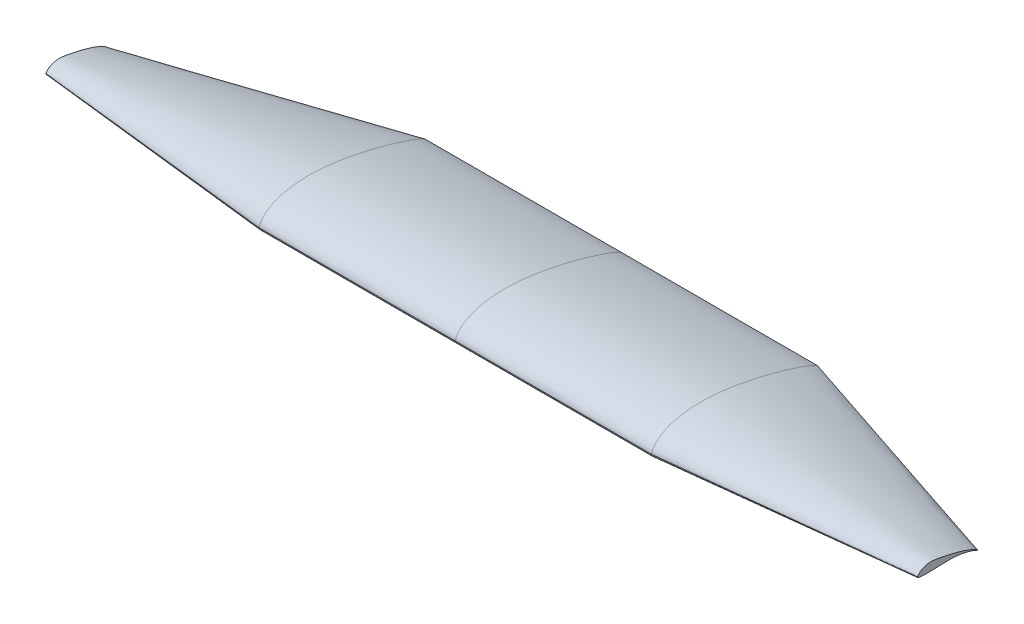
SolidWorks part; units mm, degrees
ref_plane "Front Plane" through (0, 0, 0) normal (0, 0, 1) x (1, 0, 0)
ref_plane "Top Plane" through (0, 0, 0) normal (0, 1, 0) x (1, 0, 0)
ref_plane "Right Plane" through (0, 0, 0) normal (1, 0, 0) x (0, 0, -1)
curve "Curve1"
  spline degree 3 poles (25.4, 0, 0) (25.372, 0.0127, 0) (25.2661, 0.0607, 0) (25.0476, 0.1708, 0) (24.7083, 0.3401, 0) (24.2485, 0.5327, 0) (23.6688, 0.7355, 0) (22.9732, 0.9551, 0) (22.1692, 1.1923, 0) (21.2673, 1.441, 0) (20.2799, 1.6974, 0) (19.2194, 1.9565, 0) (18.0986, 2.2117, 0) (16.9309, 2.4579, 0) (15.7293, 2.689, 0) (14.5068, 2.8993, 0) (13.2761, 3.0831, 0) (12.0499, 3.2358, 0) (10.8399, 3.3523, 0) (9.6581, 3.4292, 0) (8.5146, 3.4627, 0) (7.4185, 3.4471, 0) (6.3776, 3.3826, 0) (5.3986, 3.269, 0) (4.4879, 3.1072, 0) (3.6513, 2.8996, 0) (2.8934, 2.65, 0) (2.2179, 2.3636, 0) (1.6288, 2.0454, 0) (1.1277, 1.7031, 0) (0.7172, 1.3448, 0) (0.396, 0.9813, 0) (0.1698, 0.6239, 0) (0.0242, 0.2862, 0) (0.0082, 0.064, 0) (0.001, -0.0371, 0) knots 0 0 0 0 0.003392 0.012836 0.027012 0.045249 0.067819 0.094788 0.125784 0.160358 0.198063 0.238408 0.280877 0.324962 0.370154 0.415962 0.4619 0.507515 0.552371 0.596075 0.638248 0.678633 0.717052 0.753345 0.787382 0.819093 0.848434 0.875385 0.89998 0.922244 0.942232 0.960009 0.975549 0.988878 1 1 1 1
curve "Curve2"
  spline degree 3 poles (0.001, -0.0371, 0) (0.0123, -0.12, 0) (0.0361, -0.2949, 0) (0.317, -0.4639, 0) (0.6929, -0.5692, 0) (1.2135, -0.6662, 0) (1.8581, -0.7318, 0) (2.6218, -0.773, 0) (3.494, -0.7837, 0) (4.468, -0.7549, 0) (5.5382, -0.6866, 0) (6.7006, -0.5792, 0) (7.9499, -0.4372, 0) (9.2786, -0.2733, 0) (10.6742, -0.0995, 0) (12.1205, 0.0739, 0) (13.5986, 0.2368, 0) (15.0876, 0.3793, 0) (16.5646, 0.4933, 0) (18.0052, 0.5722, 0) (19.384, 0.6119, 0) (20.6751, 0.6102, 0) (21.8534, 0.5686, 0) (22.8944, 0.4921, 0) (23.7738, 0.3865, 0) (24.4667, 0.2603, 0) (24.9566, 0.1368, 0) (25.2443, 0.0508, 0) (25.3692, 0.0101, 0) (25.4, 0, 0) knots 0 0 0 0 0.009279 0.019577 0.035039 0.055495 0.080743 0.110498 0.144404 0.182203 0.223831 0.269139 0.318001 0.370105 0.424881 0.481621 0.539567 0.597874 0.655635 0.711901 0.765703 0.816085 0.862086 0.902834 0.937485 0.965078 0.984713 0.996231 1 1 1 1
curve "Curve3"
  spline degree 3 poles (25.4, 0, 0) (25.3455, 0.0436, 0) (25.2116, 0.1507, 0) (24.9968, 0.3329, 0) (24.7179, 0.5192, 0) (24.3838, 0.6915, 0) (23.9854, 0.8618, 0) (23.5127, 1.0388, 0) (22.9617, 1.2228, 0) (22.3389, 1.411, 0) (21.6587, 1.6, 0) (20.9384, 1.7859, 0) (20.194, 1.9655, 0) (19.4371, 2.1364, 0) (18.6752, 2.2963, 0) (17.9118, 2.4438, 0) (17.147, 2.5781, 0) (16.3791, 2.6991, 0) (15.605, 2.8074, 0) (14.8209, 2.9041, 0) (14.0236, 2.9909, 0) (13.211, 3.0702, 0) (12.3837, 3.1443, 0) (11.5456, 3.2153, 0) (10.7042, 3.2841, 0) (9.8699, 3.3504, 0) (9.0549, 3.4114, 0) (8.2722, 3.4638, 0) (7.5336, 3.5033, 0) (6.8455, 3.5244, 0) (6.2068, 3.521, 0) (5.6107, 3.49, 0) (5.0497, 3.4308, 0) (4.5176, 3.3429, 0) (4.0108, 3.2266, 0) (3.5272, 3.0823, 0) (3.0666, 2.9114, 0) (2.6305, 2.7158, 0) (2.222, 2.4994, 0) (1.8461, 2.2685, 0) (1.5081, 2.0322, 0) (1.2124, 1.7997, 0) (0.9603, 1.579, 0) (0.7502, 1.3741, 0) (0.5779, 1.1854, 0) (0.4381, 1.0119, 0) (0.3252, 0.8525, 0) (0.2341, 0.7057, 0) (0.1613, 0.5701, 0) (0.1038, 0.4444, 0) (0.0597, 0.3272, 0) (0.028, 0.2175, 0) (0.0067, 0.1145, 0) (0.002, 0.0475, 0) (-0.0002, 0.0153, 0) knots 0 0 0 0 0.007668 0.018842 0.030923 0.044413 0.060081 0.078505 0.099861 0.123886 0.149975 0.177417 0.205607 0.234111 0.262657 0.29113 0.319536 0.347958 0.376531 0.40541 0.434747 0.464647 0.495109 0.526002 0.557051 0.587854 0.61795 0.646847 0.674037 0.699207 0.722467 0.744193 0.764751 0.784417 0.803402 0.821846 0.839822 0.857338 0.87432 0.890569 0.905775 0.91961 0.931872 0.942562 0.95184 0.959925 0.96702 0.973296 0.978892 0.983919 0.988474 0.992632 0.996456 1 1 1 1
curve "Curve4"
  spline degree 3 poles (-0.0002, 0.0153, 0) (-0.0001, -0.0154, 0) (0.0001, -0.0769, 0) (0.0214, -0.1684, 0) (0.075, -0.2496, 0) (0.16, -0.3047, 0) (0.2619, -0.3388, 0) (0.378, -0.3612, 0) (0.51, -0.376, 0) (0.6617, -0.3855, 0) (0.8391, -0.3907, 0) (1.051, -0.391, 0) (1.3098, -0.3853, 0) (1.6325, -0.3717, 0) (2.0384, -0.3474, 0) (2.5403, -0.3101, 0) (3.1345, -0.2569, 0) (3.8031, -0.1837, 0) (4.5269, -0.0871, 0) (5.2942, 0.0299, 0) (6.0973, 0.1597, 0) (6.9255, 0.2967, 0) (7.7654, 0.437, 0) (8.6054, 0.5766, 0) (9.4374, 0.712, 0) (10.2578, 0.8409, 0) (11.0657, 0.9608, 0) (11.8615, 1.0703, 0) (12.6459, 1.1675, 0) (13.4202, 1.2512, 0) (14.1858, 1.3204, 0) (14.9439, 1.3743, 0) (15.6958, 1.4123, 0) (16.4425, 1.4338, 0) (17.1849, 1.4384, 0) (17.9237, 1.4258, 0) (18.659, 1.3959, 0) (19.3904, 1.3486, 0) (20.1162, 1.2841, 0) (20.833, 1.2027, 0) (21.5342, 1.1057, 0) (22.209, 0.9944, 0) (22.8431, 0.872, 0) (23.4213, 0.7417, 0) (23.9328, 0.606, 0) (24.3746, 0.4668, 0) (24.7496, 0.3244, 0) (25.0872, 0.1744, 0) (25.2937, 0.0593, 0) (25.4, 0, 0) knots 0 0 0 0 0.003545 0.0071 0.01071 0.014494 0.01858 0.023086 0.028144 0.033926 0.04066 0.048671 0.058426 0.070592 0.086022 0.105451 0.128789 0.155005 0.183229 0.21323 0.244762 0.277305 0.310312 0.343241 0.375773 0.407796 0.43928 0.470229 0.500682 0.530682 0.560295 0.589573 0.618576 0.647349 0.675954 0.704423 0.732791 0.761051 0.789175 0.817054 0.84447 0.871027 0.896137 0.919138 0.939558 0.957324 0.972672 0.985929 1 1 1 1
sketch "Sketch4" plane through (0, 0, 0) normal (0, 0, 1) x (1, 0, 0)
  spline S0 degree 3 poles (-1185.8345, -1591.3505) (49.1871, -0.0243) (32.3891, -5.936) (24.9968, 0.3329) (24.7179, 0.5192) (24.3838, 0.6915) (23.9854, 0.8618) (23.5127, 1.0388) (22.9617, 1.2228) (22.3389, 1.411) (21.6587, 1.6) (20.9384, 1.7859) (20.194, 1.9655) (19.4371, 2.1364) (18.6752, 2.2963) (17.9118, 2.4438) (17.147, 2.5781) (16.3791, 2.6991) (15.605, 2.8074) (14.8209, 2.9041) (14.0236, 2.9909) (13.211, 3.0702) (12.3837, 3.1443) (11.5456, 3.2153) (10.7042, 3.2841) (9.8699, 3.3504) (9.0549, 3.4114) (8.2722, 3.4638) (7.5336, 3.5033) (6.8455, 3.5244) (6.2068, 3.521) (5.6107, 3.49) (5.0497, 3.4308) (4.5176, 3.3429) (4.0108, 3.2266) (3.5272, 3.0823) (3.0666, 2.9114) (2.6305, 2.7158) (2.222, 2.4994) (1.8461, 2.2685) (1.5081, 2.0322) (1.2124, 1.7997) (0.9603, 1.579) (0.7502, 1.3741) (0.5779, 1.1854) (0.4381, 1.0119) (0.3252, 0.8525) (0.2341, 0.7057) (0.1613, 0.5701) (0.1038, 0.4444) (0.0597, 0.3272) (0.028, 0.2175) (-0.6393, -3.0024) (19.7265, -8.824) (-1985.4173, 239.6089) knots -1.033249 -1.033249 -1.033249 -1.033249 0.007668 0.018842 0.030923 0.044413 0.060081 0.078505 0.099861 0.123886 0.149975 0.177417 0.205607 0.234111 0.262657 0.29113 0.319536 0.347958 0.376531 0.40541 0.434747 0.464647 0.495109 0.526002 0.557051 0.587854 0.61795 0.646847 0.674037 0.699207 0.722467 0.744193 0.764751 0.784417 0.803402 0.821846 0.839822 0.857338 0.87432 0.890569 0.905775 0.91961 0.931872 0.942562 0.95184 0.959925 0.96702 0.973296 0.978892 0.983919 0.988474 0.992632 0.996456 1.348806 1.348806 1.348806 1.348806 only from (25.4, 0) to (-0.0002, 0.0153) construction
  spline S1 degree 3 poles (-1996.9046, -109.2454) (24.0142, 6.4939) (-0.5867, 2.4404) (0.0214, -0.1684) (0.075, -0.2496) (0.16, -0.3047) (0.2619, -0.3388) (0.378, -0.3612) (0.51, -0.376) (0.6617, -0.3855) (0.8391, -0.3907) (1.051, -0.391) (1.3098, -0.3853) (1.6325, -0.3717) (2.0384, -0.3474) (2.5403, -0.3101) (3.1345, -0.2569) (3.8031, -0.1837) (4.5269, -0.0871) (5.2942, 0.0299) (6.0973, 0.1597) (6.9255, 0.2967) (7.7654, 0.437) (8.6054, 0.5766) (9.4374, 0.712) (10.2578, 0.8409) (11.0657, 0.9608) (11.8615, 1.0703) (12.6459, 1.1675) (13.4202, 1.2512) (14.1858, 1.3204) (14.9439, 1.3743) (15.6958, 1.4123) (16.4425, 1.4338) (17.1849, 1.4384) (17.9237, 1.4258) (18.659, 1.3959) (19.3904, 1.3486) (20.1162, 1.2841) (20.833, 1.2027) (21.5342, 1.1057) (22.209, 0.9944) (22.8431, 0.872) (23.4213, 0.7417) (23.9328, 0.606) (24.3746, 0.4668) (24.7496, 0.3244) (32.9485, -3.3172) (27.4813, -33.5723) (953.9511, 1771.2477) knots -0.294627 -0.294627 -0.294627 -0.294627 0.003545 0.0071 0.01071 0.014494 0.01858 0.023086 0.028144 0.033926 0.04066 0.048671 0.058426 0.070592 0.086022 0.105451 0.128789 0.155005 0.183229 0.21323 0.244762 0.277305 0.310312 0.343241 0.375773 0.407796 0.43928 0.470229 0.500682 0.530682 0.560295 0.589573 0.618576 0.647349 0.675954 0.704423 0.732791 0.761051 0.789175 0.817054 0.84447 0.871027 0.896137 0.919138 0.939558 0.957324 0.972672 0.985929 1.993687 1.993687 1.993687 1.993687 only from (-0.0002, 0.0153) to (25.4, 0) construction
  spline S2 degree 3 poles (25.4, 0) (25.3455, 0.0436) (25.2116, 0.1507) (24.9968, 0.3329) (24.7179, 0.5192) (24.3838, 0.6915) (23.9854, 0.8618) (23.5127, 1.0388) (22.9617, 1.2228) (22.3389, 1.411) (21.6587, 1.6) (20.9384, 1.7859) (20.194, 1.9655) (19.4371, 2.1364) (18.6752, 2.2963) (17.9118, 2.4438) (17.147, 2.5781) (16.3791, 2.6991) (15.605, 2.8074) (14.8209, 2.9041) (14.0236, 2.9909) (13.211, 3.0702) (12.3837, 3.1443) (11.5456, 3.2153) (10.7042, 3.2841) (9.8699, 3.3504) (9.0549, 3.4114) (8.2722, 3.4638) (7.5336, 3.5033) (6.8455, 3.5244) (6.2068, 3.521) (5.6107, 3.49) (5.0497, 3.4308) (4.5176, 3.3429) (4.0108, 3.2266) (3.5272, 3.0823) (3.0666, 2.9114) (2.6305, 2.7158) (2.222, 2.4994) (1.8461, 2.2685) (1.5081, 2.0322) (1.2124, 1.7997) (0.9603, 1.579) (0.7502, 1.3741) (0.5779, 1.1854) (0.4381, 1.0119) (0.3252, 0.8525) (0.2341, 0.7057) (0.1613, 0.5701) (0.1038, 0.4444) (0.0597, 0.3272) (0.028, 0.2175) (0.0067, 0.1145) (0.002, 0.0475) (-0.0002, 0.0153) knots 0 0 0 0 0.007668 0.018842 0.030923 0.044413 0.060081 0.078505 0.099861 0.123886 0.149975 0.177417 0.205607 0.234111 0.262657 0.29113 0.319536 0.347958 0.376531 0.40541 0.434747 0.464647 0.495109 0.526002 0.557051 0.587854 0.61795 0.646847 0.674037 0.699207 0.722467 0.744193 0.764751 0.784417 0.803402 0.821846 0.839822 0.857338 0.87432 0.890569 0.905775 0.91961 0.931872 0.942562 0.95184 0.959925 0.96702 0.973296 0.978892 0.983919 0.988474 0.992632 0.996456 1 1 1 1
  spline S3 degree 3 poles (-0.0002, 0.0153) (-0.0001, -0.0154) (0.0001, -0.0769) (0.0214, -0.1684) (0.075, -0.2496) (0.16, -0.3047) (0.2619, -0.3388) (0.378, -0.3612) (0.51, -0.376) (0.6617, -0.3855) (0.8391, -0.3907) (1.051, -0.391) (1.3098, -0.3853) (1.6325, -0.3717) (2.0384, -0.3474) (2.5403, -0.3101) (3.1345, -0.2569) (3.8031, -0.1837) (4.5269, -0.0871) (5.2942, 0.0299) (6.0973, 0.1597) (6.9255, 0.2967) (7.7654, 0.437) (8.6054, 0.5766) (9.4374, 0.712) (10.2578, 0.8409) (11.0657, 0.9608) (11.8615, 1.0703) (12.6459, 1.1675) (13.4202, 1.2512) (14.1858, 1.3204) (14.9439, 1.3743) (15.6958, 1.4123) (16.4425, 1.4338) (17.1849, 1.4384) (17.9237, 1.4258) (18.659, 1.3959) (19.3904, 1.3486) (20.1162, 1.2841) (20.833, 1.2027) (21.5342, 1.1057) (22.209, 0.9944) (22.8431, 0.872) (23.4213, 0.7417) (23.9328, 0.606) (24.3746, 0.4668) (24.7496, 0.3244) (25.0872, 0.1744) (25.2937, 0.0593) (25.4, 0) knots 0 0 0 0 0.003545 0.0071 0.01071 0.014494 0.01858 0.023086 0.028144 0.033926 0.04066 0.048671 0.058426 0.070592 0.086022 0.105451 0.128789 0.155005 0.183229 0.21323 0.244762 0.277305 0.310312 0.343241 0.375773 0.407796 0.43928 0.470229 0.500682 0.530682 0.560295 0.589573 0.618576 0.647349 0.675954 0.704423 0.732791 0.761051 0.789175 0.817054 0.84447 0.871027 0.896137 0.919138 0.939558 0.957324 0.972672 0.985929 1 1 1 1
sketch "Sketch1" plane through (0, 0, 0) normal (0, 0, 1) x (1, 0, 0)
  spline S0 degree 3 poles (-1716.1238, -1026.9999) (43.62, 33.158) (-2.8325, 1.4304) (0.317, -0.4639) (0.6929, -0.5692) (1.2135, -0.6662) (1.8581, -0.7318) (2.6218, -0.773) (3.494, -0.7837) (4.468, -0.7549) (5.5382, -0.6866) (6.7006, -0.5792) (7.9499, -0.4372) (9.2786, -0.2733) (10.6742, -0.0995) (12.1205, 0.0739) (13.5986, 0.2368) (15.0876, 0.3793) (16.5646, 0.4933) (18.0052, 0.5722) (19.384, 0.6119) (20.6751, 0.6102) (21.8534, 0.5686) (22.8944, 0.4921) (23.7738, 0.3865) (24.4667, 0.2603) (24.9566, 0.1368) (31.9392, -1.9512) (35.8158, -13.1556) (656.9828, 1897.5367) knots -0.357758 -0.357758 -0.357758 -0.357758 0.009279 0.019577 0.035039 0.055495 0.080743 0.110498 0.144404 0.182203 0.223831 0.269139 0.318001 0.370105 0.424881 0.481621 0.539567 0.597874 0.655635 0.711901 0.765703 0.816085 0.862086 0.902834 0.937485 0.965078 0.984713 0.996231 1.812784 1.812784 1.812784 1.812784 only from (0.001, -0.0371) to (25.4, 0) construction
  spline S1 degree 3 poles (-816.7312, -1813.9846) (40.2514, 5.3756) (30.2436, -2.4476) (25.0476, 0.1708) (24.7083, 0.3401) (24.2485, 0.5327) (23.6688, 0.7355) (22.9732, 0.9551) (22.1692, 1.1923) (21.2673, 1.441) (20.2799, 1.6974) (19.2194, 1.9565) (18.0986, 2.2117) (16.9309, 2.4579) (15.7293, 2.689) (14.5068, 2.8993) (13.2761, 3.0831) (12.0499, 3.2358) (10.8399, 3.3523) (9.6581, 3.4292) (8.5146, 3.4627) (7.4185, 3.4471) (6.3776, 3.3826) (5.3986, 3.269) (4.4879, 3.1072) (3.6513, 2.8996) (2.8934, 2.65) (2.2179, 2.3636) (1.6288, 2.0454) (1.1277, 1.7031) (0.7172, 1.3448) (0.396, 0.9813) (0.1698, 0.6239) (-2.024, -4.4643) (37.9783, -18.4695) (-1958.3981, 404.8989) knots -0.615231 -0.615231 -0.615231 -0.615231 0.003392 0.012836 0.027012 0.045249 0.067819 0.094788 0.125784 0.160358 0.198063 0.238408 0.280877 0.324962 0.370154 0.415962 0.4619 0.507515 0.552371 0.596075 0.638248 0.678633 0.717052 0.753345 0.787382 0.819093 0.848434 0.875385 0.89998 0.922244 0.942232 0.960009 0.975549 0.988878 1.562488 1.562488 1.562488 1.562488 only from (25.4, 0) to (0.001, -0.0371) construction
  spline S2 degree 3 poles (0.001, -0.0371) (0.0123, -0.12) (0.0361, -0.2949) (0.317, -0.4639) (0.6929, -0.5692) (1.2135, -0.6662) (1.8581, -0.7318) (2.6218, -0.773) (3.494, -0.7837) (4.468, -0.7549) (5.5382, -0.6866) (6.7006, -0.5792) (7.9499, -0.4372) (9.2786, -0.2733) (10.6742, -0.0995) (12.1205, 0.0739) (13.5986, 0.2368) (15.0876, 0.3793) (16.5646, 0.4933) (18.0052, 0.5722) (19.384, 0.6119) (20.6751, 0.6102) (21.8534, 0.5686) (22.8944, 0.4921) (23.7738, 0.3865) (24.4667, 0.2603) (24.9566, 0.1368) (25.2443, 0.0508) (25.3692, 0.0101) (25.4, 0) knots 0 0 0 0 0.009279 0.019577 0.035039 0.055495 0.080743 0.110498 0.144404 0.182203 0.223831 0.269139 0.318001 0.370105 0.424881 0.481621 0.539567 0.597874 0.655635 0.711901 0.765703 0.816085 0.862086 0.902834 0.937485 0.965078 0.984713 0.996231 1 1 1 1
  spline S3 degree 3 poles (25.4, 0) (25.372, 0.0127) (25.2661, 0.0607) (25.0476, 0.1708) (24.7083, 0.3401) (24.2485, 0.5327) (23.6688, 0.7355) (22.9732, 0.9551) (22.1692, 1.1923) (21.2673, 1.441) (20.2799, 1.6974) (19.2194, 1.9565) (18.0986, 2.2117) (16.9309, 2.4579) (15.7293, 2.689) (14.5068, 2.8993) (13.2761, 3.0831) (12.0499, 3.2358) (10.8399, 3.3523) (9.6581, 3.4292) (8.5146, 3.4627) (7.4185, 3.4471) (6.3776, 3.3826) (5.3986, 3.269) (4.4879, 3.1072) (3.6513, 2.8996) (2.8934, 2.65) (2.2179, 2.3636) (1.6288, 2.0454) (1.1277, 1.7031) (0.7172, 1.3448) (0.396, 0.9813) (0.1698, 0.6239) (0.0242, 0.2862) (0.0082, 0.064) (0.001, -0.0371) knots 0 0 0 0 0.003392 0.012836 0.027012 0.045249 0.067819 0.094788 0.125784 0.160358 0.198063 0.238408 0.280877 0.324962 0.370154 0.415962 0.4619 0.507515 0.552371 0.596075 0.638248 0.678633 0.717052 0.753345 0.787382 0.819093 0.848434 0.875385 0.89998 0.922244 0.942232 0.960009 0.975549 0.988878 1 1 1 1
sketch "Sketch2" plane through (0, 0, 0) normal (1, 0, 0) x (0, 0, -1)
  line L0 (0, 0) -> (574.8782, -20.8789) construction
  line L1 (-1000, 0) -> (49000, 0) construction
  spline S0 degree 3 poles (0, 0) (0.1844, -1.886) (0.5733, -5.865) (6.7875, -9.9296) (15.2046, -12.6352) (26.9028, -15.2746) (41.4372, -17.3102) (58.686, -18.896) (78.4169, -19.884) (100.4863, -20.0651) (124.7652, -19.4351) (151.1663, -17.9989) (179.5632, -15.852) (209.7738, -13.2791) (241.5094, -10.5383) (274.391, -7.8521) (307.983, -5.4281) (341.8055, -3.4758) (375.3321, -2.159) (408.0036, -1.606) (439.243, -1.8866) (468.4639, -3.0273) (495.0952, -4.9768) (518.5901, -7.5991) (538.4024, -10.7407) (553.9782, -14.1892) (564.9608, -17.4025) (571.3975, -19.5953) (574.1897, -20.625) (574.8782, -20.8789) knots 0 0 0 0 0.009279 0.019577 0.035039 0.055495 0.080743 0.110498 0.144404 0.182203 0.223831 0.269139 0.318001 0.370105 0.424881 0.481621 0.539567 0.597874 0.655635 0.711901 0.765703 0.816085 0.862086 0.902834 0.937485 0.965078 0.984713 0.996231 1 1 1 1
  spline S1 degree 3 poles (574.8782, -20.8789) (574.2556, -20.5679) (571.8998, -19.3911) (567.048, -16.7118) (559.513, -12.5906) (549.2719, -7.8384) (536.326, -2.7532) (520.7693, 2.8138) (502.775, 8.868) (482.5771, 15.2687) (460.4485, 21.9166) (436.6678, 28.6863) (411.5198, 35.4212) (385.3015, 41.9909) (358.3033, 48.2497) (330.8147, 54.0549) (303.1186, 59.2662) (275.496, 63.7715) (248.212, 67.4434) (221.5288, 70.1931) (195.6776, 71.9291) (170.8574, 72.5129) (147.2422, 71.9443) (124.9876, 70.2111) (104.2394, 67.3257) (85.1258, 63.3439) (67.7594, 58.3425) (52.2277, 52.4391) (38.6213, 45.7396) (26.9881, 38.4216) (17.3911, 30.6622) (9.8111, 22.712) (4.3846, 14.8166) (0.8, 7.297) (0.2501, 2.2814) (0, 0) knots 0 0 0 0 0.003392 0.012836 0.027012 0.045249 0.067819 0.094788 0.125784 0.160358 0.198063 0.238408 0.280877 0.324962 0.370154 0.415962 0.4619 0.507515 0.552371 0.596075 0.638248 0.678633 0.717052 0.753345 0.787382 0.819093 0.848434 0.875385 0.89998 0.922244 0.942232 0.960009 0.975549 0.988878 1 1 1 1
  dimension "D1" = 574.8782
  dimension "D2" = 2.08
extrude "Boss-Extrude2" add sketch "Sketch2" along normal blind 680.085
ref_plane "Plane4" through (1511.3, 0, 0) normal (1, 0, 0) x (0, 0, -1)
sketch "Sketch3" plane through (0, 0, 0) normal (0, 1, 0) x (1, 0, 0)
  line L0 (0, 143.7195) -> (1743.4724, 143.7195) construction
  line L1 (0, 574.8782) -> (0, 0) construction
  line L2 (0, 0) -> (0, 143.7195) construction
  line L3 (0, 143.7195) -> (0, 287.4391) construction
  line L4 (0, 287.4391) -> (0, 431.1586) construction
  line L5 (0, 431.1586) -> (0, 574.8782) construction
sketch "Sketch5" plane through (1511.3, 0, 0) normal (1, 0, 0) x (0, 0, -1)
  line L0 (91.459, 1.7609) -> (300.5011, -23.6544) construction
  line L1 (-1000, 1.7609) -> (49000, 1.7609) construction
  line L2 (0, 3.5219) -> (0, 0) construction
  line L3 (91.459, 1.7609) -> (91.459, 0) construction
  line L4 (91.459, 0) -> (143.7195, 0) construction
  line L5 (300.501, 0) -> (300.5011, -23.6544) construction
  line L6 (143.7195, 0) -> (195.9801, 0) construction
  line L7 (195.9801, 0) -> (248.2406, 0) construction
  line L8 (248.2406, 0) -> (300.501, 0) construction
  spline S0 degree 3 poles (300.5011, -23.6544) (300.0958, -23.2413) (299.1002, -22.2264) (297.5135, -20.5132) (295.4042, -18.702) (292.8258, -16.9516) (289.7164, -15.1529) (286.0015, -13.2252) (281.6498, -11.1627) (276.7117, -8.9931) (271.3012, -6.7607) (265.5582, -4.5132) (259.6095, -2.2936) (253.5503, -0.1341) (247.4389, 1.9405) (241.302, 3.9148) (235.1413, 5.7814) (228.9417, 7.5422) (222.6779, 9.2039) (216.3211, 10.7807) (209.8449, 12.2891) (203.2356, 13.7504) (196.5001, 15.184) (189.673, 16.6029) (182.8167, 18.0074) (176.0159, 19.3831) (169.3684, 20.6971) (162.9784, 21.9074) (156.9388, 22.9679) (151.2966, 23.8264) (146.0361, 24.4347) (141.0995, 24.7732) (136.4228, 24.8441) (131.9562, 24.6508) (127.6688, 24.1978) (123.5449, 23.4916) (119.5836, 22.5439) (115.7994, 21.368) (112.2223, 19.9935) (108.8983, 18.4677) (105.8808, 16.8589) (103.2157, 15.2399) (100.9214, 13.6749) (98.9882, 12.197) (97.3824, 10.8155) (96.0591, 9.5273) (94.9705, 8.3273) (94.0751, 7.2096) (93.3405, 6.1662) (92.7421, 5.1887) (92.2628, 4.2681) (91.8927, 3.3968) (91.6145, 2.5704) (91.5095, 2.0238) (91.459, 1.7609) knots 0 0 0 0 0.007668 0.018842 0.030923 0.044413 0.060081 0.078505 0.099861 0.123886 0.149975 0.177417 0.205607 0.234111 0.262657 0.29113 0.319536 0.347958 0.376531 0.40541 0.434747 0.464647 0.495109 0.526002 0.557051 0.587854 0.61795 0.646847 0.674037 0.699207 0.722467 0.744193 0.764751 0.784417 0.803402 0.821846 0.839822 0.857338 0.87432 0.890569 0.905775 0.91961 0.931872 0.942562 0.95184 0.959925 0.96702 0.973296 0.978892 0.983919 0.988474 0.992632 0.996456 1 1 1 1
  spline S1 degree 3 poles (91.459, 1.7609) (91.4293, 1.5082) (91.3696, 1.002) (91.454, 0.2276) (91.8142, -0.4943) (92.4591, -1.0326) (93.264, -1.4149) (94.1972, -1.715) (95.2684, -1.9681) (96.5076, -2.1973) (97.963, -2.4164) (99.7066, -2.6296) (101.8422, -2.8405) (104.5118, -3.0498) (107.8769, -3.2544) (112.0448, -3.447) (116.988, -3.6008) (122.564, -3.6635) (128.6176, -3.589) (135.0493, -3.3905) (141.7883, -3.1218) (148.7414, -2.8182) (155.7941, -2.5) (162.8463, -2.1875) (169.829, -1.901) (176.7098, -1.6573) (183.4789, -1.4744) (190.1372, -1.3661) (196.69, -1.3471) (203.1465, -1.4292) (209.5165, -1.6213) (215.8103, -1.9327) (222.0364, -2.3685) (228.2036, -2.9352) (234.3183, -3.6365) (240.3864, -4.4758) (246.4086, -5.4539) (252.3814, -6.5713) (258.2913, -7.8245) (264.11, -9.2082) (269.7844, -10.705) (275.2278, -12.2926) (280.3244, -13.9314) (284.9536, -15.5798) (289.0288, -17.2056) (292.526, -18.7913) (295.4705, -20.3371) (298.1, -21.9075) (299.685, -23.0606) (300.5011, -23.6544) knots 0 0 0 0 0.003545 0.0071 0.01071 0.014494 0.01858 0.023086 0.028144 0.033926 0.04066 0.048671 0.058426 0.070592 0.086022 0.105451 0.128789 0.155005 0.183229 0.21323 0.244762 0.277305 0.310312 0.343241 0.375773 0.407796 0.43928 0.470229 0.500682 0.530682 0.560295 0.589573 0.618576 0.647349 0.675954 0.704423 0.732791 0.761051 0.789175 0.817054 0.84447 0.871027 0.896137 0.919138 0.939558 0.957324 0.972672 0.985929 1 1 1 1
  point P7 (0, 1.7609)
  dimension "D1" = 209.042
  dimension "D2" = 25.4153
sketch "Sketch6" plane through (680.085, 0, 0) normal (1, 0, 0) x (0, 0, -1)
  spline S2 degree 3 poles (-673.7077, -2745.8479) (684.4763, -29.9694) (616.59, -44.0701) (567.048, -16.7118) (559.513, -12.5906) (549.2719, -7.8384) (536.326, -2.7532) (520.7693, 2.8138) (502.775, 8.868) (482.5771, 15.2687) (460.4485, 21.9166) (436.6678, 28.6863) (411.5198, 35.4212) (385.3015, 41.9909) (358.3033, 48.2497) (330.8147, 54.0549) (303.1186, 59.2662) (275.496, 63.7715) (248.212, 67.4434) (221.5288, 70.1931) (195.6776, 71.9291) (170.8574, 72.5129) (147.2422, 71.9443) (124.9876, 70.2111) (104.2394, 67.3257) (85.1258, 63.3439) (67.7594, 58.3425) (52.2277, 52.4391) (38.6213, 45.7396) (26.9881, 38.4216) (17.3911, 30.6622) (9.8111, 22.712) (4.3846, 14.8166) (-19.6237, -35.5476) (132.5736, -127.4912) (-2936.2723, 603.3427) knots -0.248804 -0.248804 -0.248804 -0.248804 0.003392 0.012836 0.027012 0.045249 0.067819 0.094788 0.125784 0.160358 0.198063 0.238408 0.280877 0.324962 0.370154 0.415962 0.4619 0.507515 0.552371 0.596075 0.638248 0.678633 0.717052 0.753345 0.787382 0.819093 0.848434 0.875385 0.89998 0.922244 0.942232 0.960009 0.975549 0.988878 1.227859 1.227859 1.227859 1.227859 only from (574.8782, -20.8789) to (0, 0)
  spline S3 degree 3 poles (-2661.3608, -1381.1653) (163.9668, 151.0666) (-25.1742, 10.9758) (6.7875, -9.9296) (15.2046, -12.6352) (26.9028, -15.2746) (41.4372, -17.3102) (58.686, -18.896) (78.4169, -19.884) (100.4863, -20.0651) (124.7652, -19.4351) (151.1663, -17.9989) (179.5632, -15.852) (209.7738, -13.2791) (241.5094, -10.5383) (274.391, -7.8521) (307.983, -5.4281) (341.8055, -3.4758) (375.3321, -2.159) (408.0036, -1.606) (439.243, -1.8866) (468.4639, -3.0273) (495.0952, -4.9768) (518.5901, -7.5991) (538.4024, -10.7407) (553.9782, -14.1892) (564.9608, -17.4025) (631.9494, -40.2234) (682.4818, -97.1332) (1776.5148, 2723.7464) knots -0.145177 -0.145177 -0.145177 -0.145177 0.009279 0.019577 0.035039 0.055495 0.080743 0.110498 0.144404 0.182203 0.223831 0.269139 0.318001 0.370105 0.424881 0.481621 0.539567 0.597874 0.655635 0.711901 0.765703 0.816085 0.862086 0.902834 0.937485 0.965078 0.984713 0.996231 1.328518 1.328518 1.328518 1.328518 only from (0, 0) to (574.8782, -20.8789)
  spline S4 degree 3 poles (574.8782, -20.8789) (574.2556, -20.5679) (571.8998, -19.3911) (567.048, -16.7118) (559.513, -12.5906) (549.2719, -7.8384) (536.326, -2.7532) (520.7693, 2.8138) (502.775, 8.868) (482.5771, 15.2687) (460.4485, 21.9166) (436.6678, 28.6863) (411.5198, 35.4212) (385.3015, 41.9909) (358.3033, 48.2497) (330.8147, 54.0549) (303.1186, 59.2662) (275.496, 63.7715) (248.212, 67.4434) (221.5288, 70.1931) (195.6776, 71.9291) (170.8574, 72.5129) (147.2422, 71.9443) (124.9876, 70.2111) (104.2394, 67.3257) (85.1258, 63.3439) (67.7594, 58.3425) (52.2277, 52.4391) (38.6213, 45.7396) (26.9881, 38.4216) (17.3911, 30.6622) (9.8111, 22.712) (4.3846, 14.8166) (0.8, 7.297) (0.2501, 2.2814) (0, 0) knots 0 0 0 0 0.003392 0.012836 0.027012 0.045249 0.067819 0.094788 0.125784 0.160358 0.198063 0.238408 0.280877 0.324962 0.370154 0.415962 0.4619 0.507515 0.552371 0.596075 0.638248 0.678633 0.717052 0.753345 0.787382 0.819093 0.848434 0.875385 0.89998 0.922244 0.942232 0.960009 0.975549 0.988878 1 1 1 1
  spline S5 degree 3 poles (0, 0) (0.1844, -1.886) (0.5733, -5.865) (6.7875, -9.9296) (15.2046, -12.6352) (26.9028, -15.2746) (41.4372, -17.3102) (58.686, -18.896) (78.4169, -19.884) (100.4863, -20.0651) (124.7652, -19.4351) (151.1663, -17.9989) (179.5632, -15.852) (209.7738, -13.2791) (241.5094, -10.5383) (274.391, -7.8521) (307.983, -5.4281) (341.8055, -3.4758) (375.3321, -2.159) (408.0036, -1.606) (439.243, -1.8866) (468.4639, -3.0273) (495.0952, -4.9768) (518.5901, -7.5991) (538.4024, -10.7407) (553.9782, -14.1892) (564.9608, -17.4025) (571.3975, -19.5953) (574.1897, -20.625) (574.8782, -20.8789) knots 0 0 0 0 0.009279 0.019577 0.035039 0.055495 0.080743 0.110498 0.144404 0.182203 0.223831 0.269139 0.318001 0.370105 0.424881 0.481621 0.539567 0.597874 0.655635 0.711901 0.765703 0.816085 0.862086 0.902834 0.937485 0.965078 0.984713 0.996231 1 1 1 1
  dimension "D1" = 0
loft "Loft1" add profiles "Sketch5", "Sketch6"
ref_plane "Plane5" through (190.5, 0, 0) normal (1, 0, 0) x (0, 0, -1)
mirror "Mirror1" about plane through (0, 0, 0) normal (1, 0, 0) of bodies 102 103
equation "\"root twist\"= 2deg"
equation "\"rootchord\"= 22.633in"
equation "\"constantchord\"= 26.775in"
equation "\"D2@Sketch2\"= \"root twist\"+ 0.08365512deg"
equation "\"D1@Boss-Extrude2\"=\"constantchord\""
equation "\"tipchord\"=8.23"
equation "\"D1@Sketch5\"=\"tipchord\""
equation "\"tiptwist\"= 1deg"
